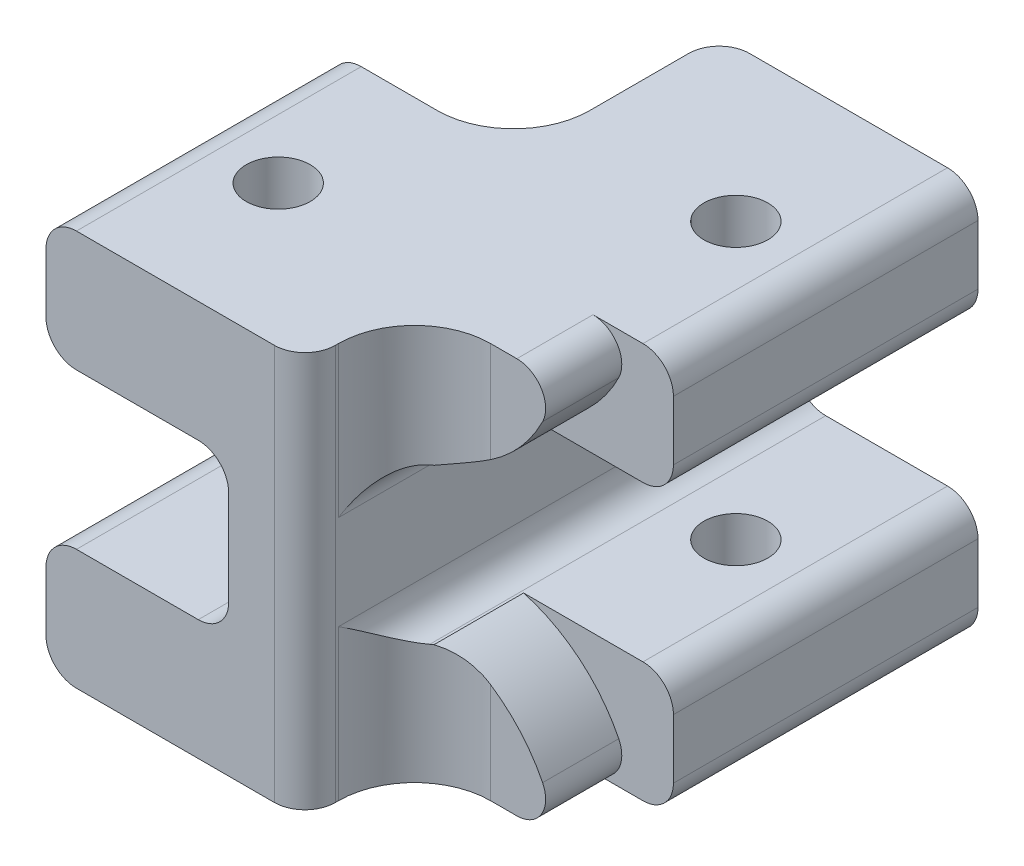
SolidWorks part; units mm, degrees
ref_plane "Front Plane" through (0, 0, 0) normal (0, 0, 1) x (1, 0, 0)
ref_plane "Top Plane" through (0, 0, 0) normal (0, 1, 0) x (1, 0, 0)
ref_plane "Right Plane" through (0, 0, 0) normal (1, 0, 0) x (0, 0, -1)
sketch "Sketch1" plane through (0, 0, 0) normal (0, 0, 1) x (1, 0, 0)
  line L0 (2.5, 13) -> (14.5, 13)
  line L1 (-2.5, -13) -> (2.5, -13)
  line L2 (-2.5, -13) -> (-2.5, 13)
  line L3 (-2.5, 13) -> (2.5, 13)
  line L4 (2.5, -13) -> (2.5, 13)
  line L5 (-2.5, -13) -> (2.5, 13) construction
  line L6 (-2.5, 13) -> (2.5, -13) construction
  line L7 (-2.5, 0) -> (2.5, 0) construction
  line L8 (14.5, 13) -> (14.5, 5.1)
  line L9 (14.5, 5.1) -> (2.5, 5.1)
  line L10 (2.5, -13) -> (14.5, -13)
  line L11 (14.5, -13) -> (14.5, -5.1)
  line L12 (14.5, -5.1) -> (2.5, -5.1)
  line L13 (0, 13) -> (0, -13) construction
  line L14 (2.5, 13) -> (-2.5, -13) construction
  line L15 (2.5, -13) -> (-2.5, 13) construction
  line L16 (-14.5, -5.1) -> (-2.5, -5.1)
  line L17 (-14.5, -13) -> (-14.5, -5.1)
  line L18 (-2.5, -13) -> (-14.5, -13)
  line L19 (-14.5, 5.1) -> (-2.5, 5.1)
  line L20 (-14.5, 13) -> (-14.5, 5.1)
  line L21 (-2.5, -13) -> (-2.5, 13)
  line L22 (-2.5, 13) -> (-14.5, 13)
  point P0 (0, 0)
  dimension "D1" = 26
  dimension "D2" = 5
  dimension "D3" = 12
  dimension "D4" = 7.9
extrude "Boss-Extrude1" add sketch "Sketch1" along normal blind 20 contours L1 L4 L3 L2 | L9 L8 L0 L4 | L11 L12 L4 L10
fillet "Fillet2" [suppressed] radius 2
sketch "Sketch2" [suppressed] plane through (0, 0, 0) normal (0, 1, 0) x (1, 0, 0)
  line L0 (-8.6, -10) -> (-14.5, -10) construction
  line L2 (-14.5, 0) -> (-14.5, -20) construction
  line L3 (-14.5, 0) -> (-14.5, -20)
  circle A0 centre (-8.6, -10) radius 2.1
  dimension "D1" = 4.2
  dimension "D2" = 5.9
extrude "Cut-Extrude1" [suppressed] cut sketch "Sketch2" against normal through all both and the other way through all
mirror "Mirror1" [suppressed] about plane through (0, 0, 0) normal (1, 0, 0)
fillet "Fillet3" [suppressed] radius 1
sketch "Sketch3" plane through (0, 0, 20) normal (0, 0, 1) x (1, 0, 0)
  line L0 (2.5, -13) -> (2.5, 13) construction
  line L1 (0, -13) -> (0, 13) construction
  line L2 (2.5, 13) -> (2.5, -13)
  line L3 (-14.5, 13) -> (2.5, 13)
  line L4 (-14.5, 5.1) -> (-14.5, 13)
  line L5 (-2.5, 5.1) -> (-14.5, 5.1)
  line L6 (-2.5, -5.1) -> (-2.5, 5.1)
  line L7 (-14.5, -5.1) -> (-2.5, -5.1)
  line L8 (-2.5, -13) -> (14.5, -13)
  line L9 (14.5, -13) -> (14.5, -5.1)
  line L10 (14.5, -5.1) -> (2.5, -5.1)
  line L11 (2.5, -5.1) -> (2.5, 5.1)
  line L12 (2.5, 5.1) -> (14.5, 5.1)
  line L13 (14.5, 5.1) -> (14.5, 13)
  line L14 (14.5, 13) -> (-2.5, 13)
  line L15 (-2.5, 13) -> (-2.5, -13)
  line L16 (-2.5, -13) -> (14.5, -13)
  line L17 (14.5, -13) -> (14.5, -5.1)
  line L18 (14.5, -5.1) -> (2.5, -5.1)
  line L19 (2.5, -5.1) -> (2.5, 5.1)
  line L20 (2.5, 5.1) -> (14.5, 5.1)
  line L21 (14.5, 5.1) -> (14.5, 13)
  line L22 (14.5, 13) -> (-2.5, 13)
  line L23 (-2.5, 13) -> (-2.5, -13)
  line L24 (-14.5, -13) -> (-14.5, -5.1)
  line L25 (2.5, -13) -> (-14.5, -13)
  dimension "D1" = 0
extrude "Boss-Extrude3" add sketch "Sketch3" against normal blind 6.5 and the other way blind 12.2 contours L25 L10 L7 L24 | L5 L10 L3 L4 | L2 L9 L10 L7 L4
sketch "Sketch4" plane through (0, 0, 0) normal (0, 1, 0) x (1, 0, 0)
  line L0 (14.5, -20) -> (14.5, 0) construction
  line L1 (14.5, -20) -> (14.5, 0)
  line L2 (2.5, -20) -> (2.5, 0) construction
  line L3 (2.5, -20) -> (2.5, 0)
  line L4 (14.5, -10) -> (2.5, -10) construction
  line L5 (-14.5, -32.2) -> (-14.5, -13.5) construction
  line L6 (-14.5, -32.2) -> (-14.5, -13.5)
  line L7 (-14.5, -22.85) -> (2.5, -22.85) construction
  line L8 (2.5, -32.2) -> (2.5, -20) construction
  circle A0 centre (8.6, -10) radius 2.1
  circle A1 centre (-8.6, -22.85) radius 2.1
  dimension "D1" = 4.2
  dimension "D3" = 4.2
  dimension "D2" = 5.9
  dimension "D4" = 5.9
extrude "Cut-Extrude2" cut sketch "Sketch4" against normal through all both and the other way through all contours A0 | A1
fillet "Fillet5" radius 2 12 edges at (14.5, 13, 10) (14.5, 5.1, 10) (2.5, 5.1, 10) (2.5, -5.1, 10) (14.5, -5.1, 10) (14.5, -13, 10) (-2.5, 5.1, 22.85) (-14.5, -13, 22.85) (-14.5, 13, 22.85) (-14.5, 5.1, 22.85) (-2.5, -5.1, 22.85) (-14.5, -5.1, 22.85)
fillet "Fillet7" radius 2 2 edges at (2.5, 0, 32.2) (-2.5, 0, 0)
sketch "Sketch8" plane through (0, 0, 20) normal (0, 0, 1) x (1, 0, 0)
  line L1 (2.5, 13) -> (2.5, -13) construction
  line L2 (2.5, 13) -> (2.5, -13)
  line L4 (2.5, 3) -> (2.5, -3)
  line L7 (14.5, -11) -> (14.5, -7.1)
  line L8 (12.5, -5.1) -> (4.5, -5.1)
  line L9 (2.5, -3.1) -> (2.5, -13)
  line L10 (2.5, -13) -> (12.5, -13)
  line L11 (14.5, -11) -> (14.5, -7.1)
  line L12 (12.5, -5.1) -> (4.5, -5.1)
  line L13 (2.5, -3.1) -> (2.5, -13)
  line L14 (2.5, -13) -> (12.5, -13)
  line L15 (14.5, 7.1) -> (14.5, 11)
  line L16 (12.5, 13) -> (2.5, 13)
  line L17 (2.5, 13) -> (2.5, 3.1)
  line L18 (4.5, 5.1) -> (12.5, 5.1)
  line L19 (14.5, 7.1) -> (14.5, 11)
  line L20 (12.5, 13) -> (2.5, 13)
  line L21 (2.5, 13) -> (2.5, 3.1)
  line L22 (4.5, 5.1) -> (12.5, 5.1)
  arc A5 (10.9105, 10.2653) -> (9.2185, 13) centre (9.2185, 11.1092) ccw
  arc A6 (10.9105, -10.2653) -> (9.2185, -13) centre (9.2185, -11.1092) cw
  arc A7 (10.9105, -10.2653) -> (53.0056, -8.1359) centre (31.4926, 0) ccw
  arc A8 (14.5, -7.1) -> (12.5, -5.1) centre (12.5, -7.1) ccw
  arc A9 (2.5, -3.1) -> (4.5, -5.1) centre (4.5, -3.1) ccw
  arc A10 (12.5, -13) -> (14.5, -11) centre (12.5, -11) ccw
  arc A11 (14.5, -7.1) -> (12.5, -5.1) centre (12.5, -7.1) ccw
  arc A12 (2.5, -3.1) -> (4.5, -5.1) centre (4.5, -3.1) ccw
  arc A13 (12.5, -13) -> (14.5, -11) centre (12.5, -11) ccw
  arc A14 (14.5, 11) -> (12.5, 13) centre (12.5, 11) ccw
  arc A15 (4.5, 5.1) -> (2.5, 3.1) centre (4.5, 3.1) ccw
  arc A16 (12.5, 5.1) -> (14.5, 7.1) centre (12.5, 7.1) ccw
  arc A17 (14.5, 11) -> (12.5, 13) centre (12.5, 11) ccw
  arc A18 (4.5, 5.1) -> (2.5, 3.1) centre (4.5, 3.1) ccw
  arc A19 (12.5, 5.1) -> (14.5, 7.1) centre (12.5, 7.1) ccw
  arc A20 (53.8507, -7.1264) -> (53.0056, -8.1359) centre (54.8763, -8.8434) ccw
  arc A21 (53.8507, -7.1264) -> (53.8507, 7.1264) centre (31.4926, 0) ccw
  arc A22 (53.0056, 8.1359) -> (53.8507, 7.1264) centre (54.8763, 8.8434) ccw
  arc A23 (53.0056, 8.1359) -> (10.9105, 10.2653) centre (31.4926, 0) ccw
  arc A24 (4.077, 4.9547) -> (10.9105, 10.2653) centre (1.9618, 14.7285) ccw
  arc A25 (4.077, 4.9547) -> (2.5, 3) centre (4.5, 3) ccw
  arc A26 (2.5, -3) -> (4.077, -4.9547) centre (4.5, -3) ccw
  arc A27 (10.9105, -10.2653) -> (4.077, -4.9547) centre (1.9618, -14.7285) ccw
  dimension "D1" = 0
  dimension "D2" = 0
extrude "Boss-Extrude5" add sketch "Sketch8" along normal blind 5
fillet "Fillet15" radius 5 4 edges at (-2.5, -8.05, 13.5) (-2.5, 8.05, 13.5) (2.5, -8.05, 25) (2.5, 8.05, 25)
